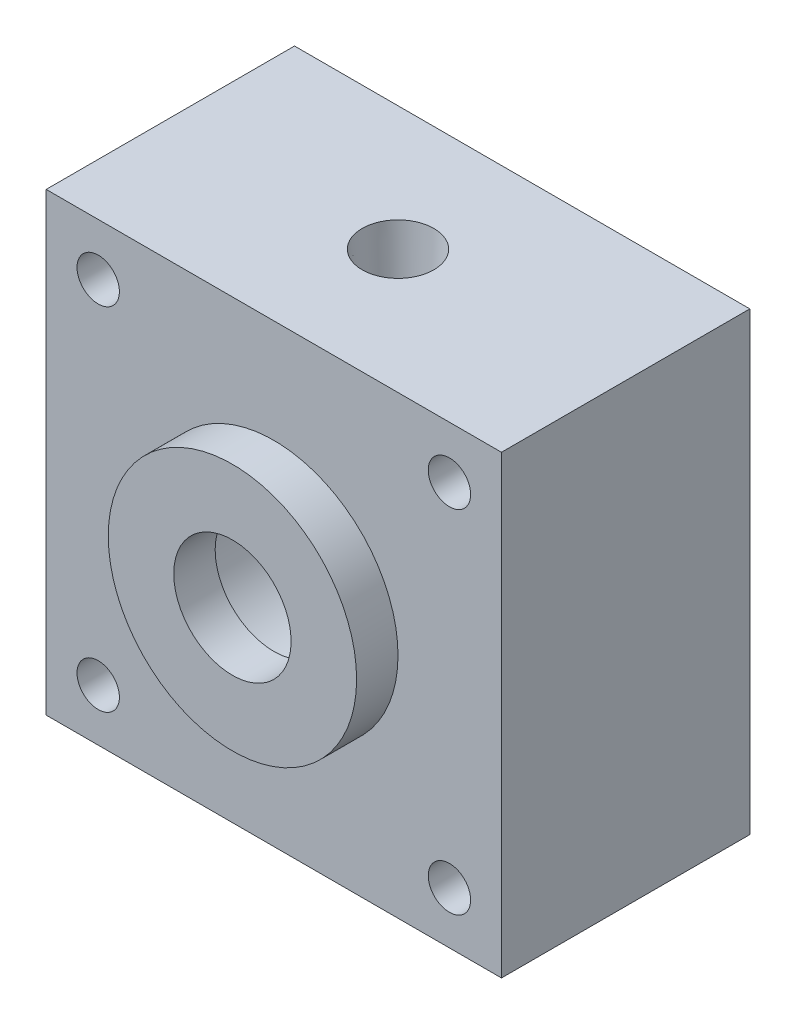
SolidWorks part; units mm, degrees
ref_plane "Front" through (0, 0, 0) normal (0, 0, 1) x (1, 0, 0)
ref_plane "Top" through (0, 0, 0) normal (0, 1, 0) x (1, 0, 0)
ref_plane "Right" through (0, 0, 0) normal (1, 0, 0) x (0, 0, -1)
sketch "Sketch1" plane through (0, 0, 0) normal (0, 0, 1) x (1, 0, 0)
  line L0 (-17.4625, 17.4625) -> (17.4625, 17.4625)
  line L1 (-17.4625, 17.4625) -> (-17.4625, -17.4625)
  line L2 (17.4625, -17.4625) -> (-17.4625, -17.4625)
  line L3 (17.4625, -17.4625) -> (17.4625, 17.4625)
  line L4 (17.4625, 17.4625) -> (-17.4625, -17.4625) construction
  dimension "D1" = 34.925
extrude "Base-Extrude" add sketch "Sketch1" along normal blind 19.05
sketch "Sketch12" plane through (-5.9785, 12.8213, 0) normal (0, 0, -1) x (-1, 0, 0)
  circle A0 centre (-5.9785, -12.8213) radius 14.25
  circle A1 centre (-5.9785, -12.8213) radius 15.875
  dimension "D1" = 28.5
  dimension "D2" = 31.75
extrude "Cut-Extrude4" cut sketch "Sketch12" against normal blind 1.524
sketch "Sketch3" plane through (0, 0, 19.05) normal (0, 0, 1) x (1, 0, 0)
  line L0 (0, 0) -> (17.4625, 17.4625) construction
  circle A0 centre (13.4704, 13.4704) radius 1.625
  circle A1 centre (0, 0) radius 19.05 construction
  dimension "D1" = 3.25
  dimension "D2" = 38.1
extrude "Cut-Extrude2" cut sketch "Sketch3" against normal through all
pattern_circular "CirPattern2" count 4 every 90 about axis through (0, 0, 0) along (0, 0, 1) of "Cut-Extrude2"
hole_wizard "Hole3" positions "Sketch9" profile "Sketch10" legacy
sketch "Sketch9" plane through (5.4711, 17.4625, 3.5795) normal (0, 1, 0) x (-1, 0, 0)
  line L1 (5.4711, 5.9455) -> (22.9336, 5.9455) construction
  line L3 (22.9336, 15.4705) -> (22.9336, -3.5795) construction
  line L4 (5.4711, -2.0555) -> (5.4711, -3.5795) construction
  point P0 (5.4711, 5.9455)
sketch "Sketch10" plane through (0, 17.4625, 9.525) normal (1, 0, 0) x (0, 0, 1)
  line L0 (0, 0) -> (0, 7.7999)
  line L1 (0, 7.7999) -> (2.413, 6.35)
  line L2 (2.413, 6.35) -> (2.413, 4.826)
  line L4 (2.7505, 0) -> (0, 0)
  line L5 (0, -4.0065) -> (0, 25.3083) construction
  line L6 (0, 7.7999) -> (-2.413, 6.35) construction
  line L7 (2.413, 4.826) -> (2.7505, 0)
  dimension "Depth" = 6.35
  dimension "Drill Angle" = 118
  dimension "Diameter" = 4.826
sketch "Sketch15" plane through (0, 0, 19.05) normal (0, 0, 1) x (1, 0, 0)
  circle A0 centre (0, 0) radius 9.525
  dimension "D1" = 19.05
extrude "Boss-Extrude1" add sketch "Sketch15" along normal blind 3.175
sketch "Sketch14" plane through (0, 0, 0) normal (0, 0, -1) x (-1, 0, 0)
  circle A0 centre (0, 0) radius 4.5
  dimension "D1" = 9
extrude "Cut-Extrude6" cut sketch "Sketch14" against normal through all
sketch "Sketch16" plane through (0, 0, 0) normal (0, 0, -1) x (-1, 0, 0)
  circle A0 centre (0, 0) radius 6.35
  dimension "D1" = 12.7
extrude "Cut-Extrude7" cut sketch "Sketch16" against normal up to surface (19.05 mm away)
sketch "Sketch17" plane through (0, 0, 0) normal (1, 0, 0) x (0, 0, -1)
  line L0 (-9.525, 11.1125) -> (-1.9489, -2.0097) construction
  line L1 (-9.525, 11.1125) -> (-9.525, 9.6626) construction
  line L2 (-9.525, 11.1125) -> (-10.5149, 10.541)
  line L3 (-11.938, 11.1125) -> (-7.112, 11.1125) construction
  line L4 (-10.5149, 10.541) -> (-4.0991, -0.5715)
  line L5 (-4.0991, -0.5715) -> (-3.1092, 0)
  line L6 (-3.1092, 0) -> (-9.525, 11.1125)
  line L7 (0, 0) -> (-24.9573, 0) construction
  line L8 (-22.225, 0) -> (-19.05, 0) construction
  dimension "D1" = 2.286
  dimension "D2" = 60
revolve "Cut-Revolve1" cut sketch "Sketch17" angle 360 about L0
